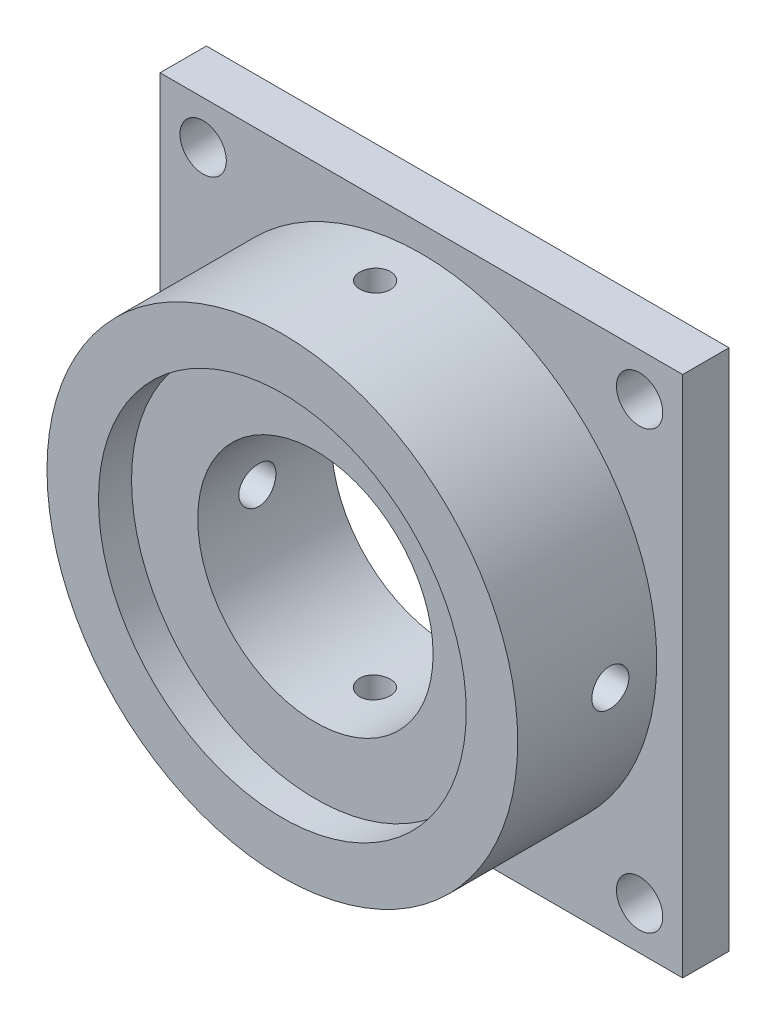
SolidWorks part; units mm, degrees
material "AISI 316 Stainless Steel Sheet (SS)"
ref_plane "Front Plane" through (0, 0, 0) normal (0, 0, 1) x (1, 0, 0)
ref_plane "Top Plane" through (0, 0, 0) normal (0, 1, 0) x (1, 0, 0)
ref_plane "Right Plane" through (0, 0, 0) normal (1, 0, 0) x (0, 0, -1)
sketch "Sketch1" plane through (0, 0, 0) normal (0, 0, 1) x (1, 0, 0)
  circle A0 centre (0, 0) radius 25.4
  circle A1 centre (0, 0) radius 12.7
  circle A3 centre (0, 0) radius 12.7
  circle A5 centre (0, 0) radius 12.7
  circle A7 centre (0, 0) radius 12.7
  point P18 (0, 0)
  dimension "D1" = 50.8
  dimension "D2" = 25.4
extrude "Boss-Extrude1" add sketch "Sketch1" along normal blind 20
sketch "Sketch2" plane through (0, 0, 0) normal (1, 0, 0) x (0, 0, -1)
  circle A0 centre (-10, 0) radius 2
  dimension "D1" = 4
  dimension "D2" = 10
extrude "Cut-Extrude1" cut sketch "Sketch2" against normal mid plane 60
sketch "Sketch3" plane through (0, 0, 20) normal (0, 0, 1) x (1, 0, 0)
  circle A0 centre (0, 0) radius 19.8438
  circle A1 centre (0, 0) radius 12.7 construction
  circle A2 centre (0, 0) radius 12.7
  dimension "D1" = 39.6875
extrude "Cut-Extrude2" cut sketch "Sketch3" against normal blind 3.5687
sketch "Sketch5" plane through (0, 0, 0) normal (0, 1, 0) x (1, 0, 0)
  line L0 (-25.4, -20) -> (25.4, -20) construction
  circle A0 centre (0, -10) radius 1.65
  dimension "D1" = 3.3
  dimension "D2" = 10
extrude "Cut-Extrude4" cut sketch "Sketch5" against normal mid plane 63.4
sketch "Sketch6" plane through (0, 0, 0) normal (0, 0, -1) x (-1, 0, 0)
  line L1 (-28.2, -28.2) -> (28.2, -28.2)
  line L2 (-28.2, -28.2) -> (-28.2, 28.2)
  line L3 (-28.2, 28.2) -> (28.2, 28.2)
  line L4 (28.2, -28.2) -> (28.2, 28.2)
  line L5 (-28.2, -28.2) -> (28.2, 28.2) construction
  line L6 (-28.2, 28.2) -> (28.2, -28.2) construction
  line L7 (-23.55, -23.55) -> (23.55, -23.55) construction
  line L8 (-23.55, -23.55) -> (-23.55, 23.55) construction
  line L9 (-23.55, 23.55) -> (23.55, 23.55) construction
  line L10 (23.55, -23.55) -> (23.55, 23.55) construction
  line L11 (-23.55, -23.55) -> (23.55, 23.55) construction
  line L12 (-23.55, 23.55) -> (23.55, -23.55) construction
  circle A0 centre (0, 0) radius 12.7
  circle A1 centre (-23.55, 23.55) radius 2.5
  circle A2 centre (23.55, 23.55) radius 2.5
  circle A3 centre (23.55, -23.55) radius 2.5
  circle A4 centre (-23.55, -23.55) radius 2.5
  point P0 (0, 0)
  dimension "D4" = 5
  dimension "D5" = 2
  dimension "D1" = 56.4
  dimension "D2" = 56.4
  dimension "D3" = 47.1
  dimension "D6" = 2
extrude "Boss-Extrude2" add sketch "Sketch6" against normal blind 5
sketch "Sketch7" plane through (0, 0, 0) normal (0, 0, -1) x (-1, 0, 0)
  circle A0 centre (0, 0) radius 19.5
  dimension "D1" = 39
extrude "Cut-Extrude5" cut sketch "Sketch7" against normal blind 2
